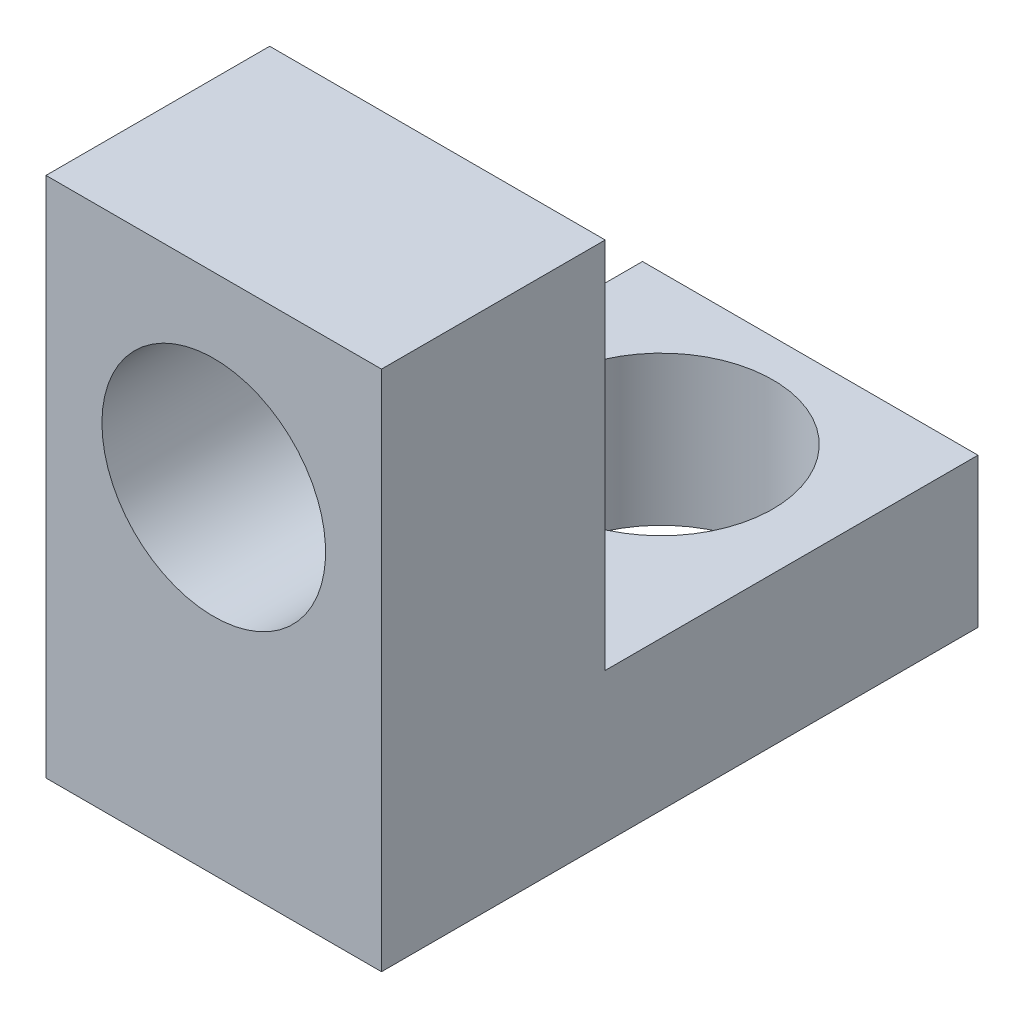
SolidWorks part; units mm, degrees
ref_plane "Front Plane" through (0, 0, 0) normal (0, 0, 1) x (1, 0, 0)
ref_plane "Top Plane" through (0, 0, 0) normal (0, 1, 0) x (1, 0, 0)
ref_plane "Right Plane" through (0, 0, 0) normal (1, 0, 0) x (0, 0, -1)
sketch "Sketch1" plane through (0, 0, 0) normal (0, 1, 0) x (1, 0, 0)
  line L1 (-2.25, 4) -> (2.25, 4)
  line L2 (-2.25, 4) -> (-2.25, -4)
  line L3 (-2.25, -4) -> (2.25, -4)
  line L4 (2.25, 4) -> (2.25, -4)
  line L5 (-2.25, 4) -> (2.25, -4) construction
  line L6 (-2.25, -4) -> (2.25, 4) construction
  point P0 (0, 0)
  dimension "D1" = 4.5
  dimension "D2" = 8
extrude "Boss-Extrude1" add sketch "Sketch1" along normal blind 2
sketch "Sketch2" plane through (0, 2, 0) normal (0, 1, 0) x (1, 0, 0)
  line L0 (-2.25, -4) -> (2.25, -4) construction
  circle A0 centre (0, 2) radius 1.5
  dimension "D2" = 3
  dimension "D1" = 6
extrude "Cut-Extrude1" cut sketch "Sketch2" against normal blind 2
sketch "Sketch3" plane through (0, 2, 0) normal (0, 1, 0) x (1, 0, 0)
  line L0 (2.25, -4) -> (2.25, 4) construction
  line L1 (-2.25, -4) -> (2.25, -4)
  line L2 (-2.25, -4) -> (-2.25, -1)
  line L3 (-2.25, -1) -> (2.25, -1)
  line L4 (2.25, -4) -> (2.25, -1)
  dimension "D1" = 3
extrude "Boss-Extrude2" add sketch "Sketch3" along normal blind 5
sketch "Sketch4" plane through (0, 0, 1) normal (0, 0, -1) x (-1, 0, 0)
  circle A0 centre (0, 4.5) radius 1.5
  dimension "D1" = 3
extrude "Cut-Extrude2" cut sketch "Sketch4" against normal blind 5
